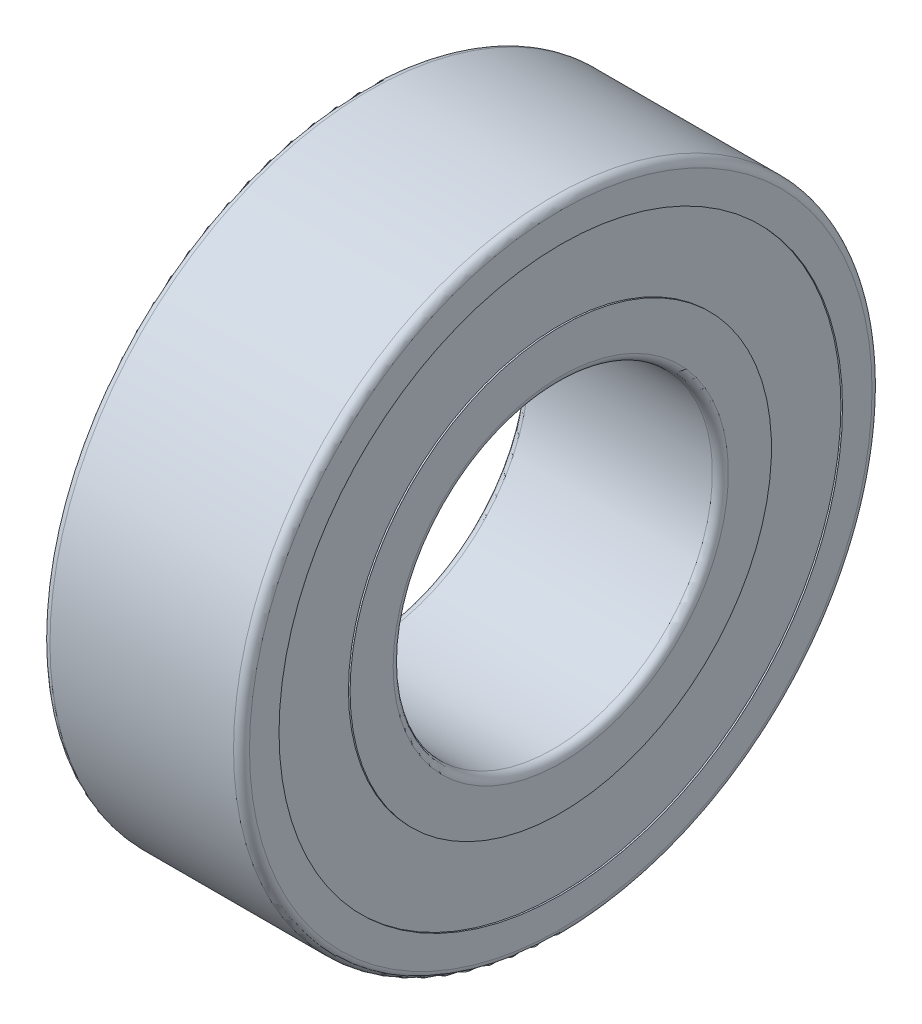
SolidWorks part; units mm, degrees
ref_plane "Front Plane" through (0, 0, 0) normal (0, 0, 1) x (1, 0, 0)
ref_plane "Top Plane" through (0, 0, 0) normal (0, 1, 0) x (1, 0, 0)
ref_plane "Right Plane" through (0, 0, 0) normal (1, 0, 0) x (0, 0, -1)
ref_plane "Plane1" through (0, 0, 0) normal (0, 0, 1) x (1, 0, 0)
sketch "Sketch1" plane through (0, 0, 0) normal (0, 0, 1) x (1, 0, 0)
  line L0 (0.2, 4) -> (4.8, 4)
  line L1 (5, 4.2) -> (5, 5.28)
  line L2 (5, 5.28) -> (4.96, 5.28)
  line L3 (4.96, 5.28) -> (4.96, 7.06)
  line L4 (4.96, 7.06) -> (5, 7.06)
  line L5 (5, 7.06) -> (5, 7.8)
  line L6 (4.8, 8) -> (0.2, 8)
  line L7 (0, 7.8) -> (0, 7.06)
  line L8 (0, 7.06) -> (0.04, 7.06)
  line L9 (0.04, 7.06) -> (0.04, 5.28)
  line L10 (0.04, 5.28) -> (0, 5.28)
  line L11 (0, 5.28) -> (0, 4.2)
  line L12 (50, 0) -> (-50, 0) construction
  arc A0 (0, 4.2) -> (0.2, 4) centre (0.2, 4.2) ccw
  arc A1 (4.8, 4) -> (5, 4.2) centre (4.8, 4.2) ccw
  arc A2 (5, 7.8) -> (4.8, 8) centre (4.8, 7.8) ccw
  arc A3 (0.2, 8) -> (0, 7.8) centre (0.2, 7.8) ccw
revolve "Revolve1" add sketch "Sketch1" angle 360 about L12
